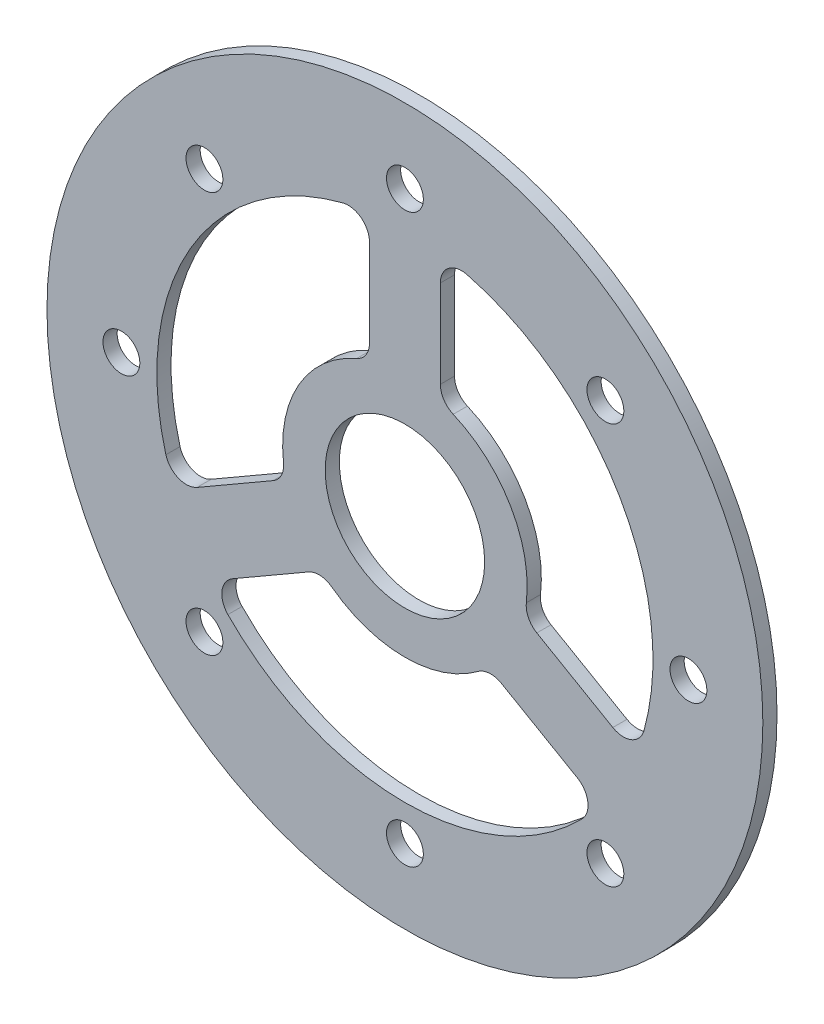
SolidWorks part; units mm, degrees
material "Thornel Mat VMA"
ref_plane "前视基准面" through (0, 0, 0) normal (0, 0, 1) x (1, 0, 0)
ref_plane "上视基准面" through (0, 0, 0) normal (0, 1, 0) x (1, 0, 0)
ref_plane "右视基准面" through (0, 0, 0) normal (1, 0, 0) x (0, 0, -1)
other "Configuration Table"
sketch "草图1" plane through (0, 0, 0) normal (0, 0, 1) x (1, 0, 0)
  circle A0 centre (0, 0) radius 40 construction
  circle A1 centre (0, 0) radius 50.5
  circle A2 centre (0, 40) radius 2.6
  circle A3 centre (0, 0) radius 35
  circle A4 centre (28.2843, 28.2843) radius 2.6
  circle A5 centre (40, 0) radius 2.6
  circle A6 centre (28.2843, -28.2843) radius 2.6
  circle A7 centre (0, -40) radius 2.6
  circle A8 centre (-28.2843, -28.2843) radius 2.6
  circle A9 centre (-40, 0) radius 2.6
  circle A10 centre (-28.2843, 28.2843) radius 2.6
  point P24 (0, 0)
  dimension "D1" = 80
  dimension "D2" = 101
  dimension "D3" = 70
  dimension "D4" = 5.2
  dimension "D5" = 8
extrude "凸台-拉伸1" add sketch "草图1" along normal blind 2
sketch "草图2" plane through (0, 0, 2) normal (0, 0, 1) x (1, 0, 0)
  line L0 (0, 35) -> (0, 17.25) construction
  line L1 (-5, 34.641) -> (-5, 17.25)
  line L2 (5, 34.641) -> (5, 17.25)
  line L3 (-5, 35) -> (-5, 17.25) construction
  line L4 (5, 35) -> (5, 17.25) construction
  line L5 (-5, 17.25) -> (-5, 16.5095)
  line L6 (5, 17.25) -> (5, 16.5095)
  line L7 (32.5, -12.9904) -> (17.4389, -4.2949)
  line L8 (27.5, -21.6506) -> (12.4389, -12.9551)
  line L9 (30.3109, -17.5) -> (14.9389, -8.625) construction
  line L10 (17.4389, -4.2949) -> (16.7976, -3.9246)
  line L11 (12.4389, -12.9551) -> (11.7976, -12.5849)
  line L12 (-27.5, -21.6506) -> (-12.4389, -12.9551)
  line L13 (-32.5, -12.9904) -> (-17.4389, -4.2949)
  line L14 (-30.3109, -17.5) -> (-14.9389, -8.625) construction
  line L15 (-12.4389, -12.9551) -> (-11.7976, -12.5849)
  line L16 (-17.4389, -4.2949) -> (-16.7976, -3.9246)
  circle A0 centre (0, 0) radius 17.5 construction
  circle A1 centre (0, 17.5) radius 2.55 construction
  circle A4 centre (15.1554, -8.75) radius 2.55 construction
  circle A5 centre (-15.1554, -8.75) radius 2.55 construction
  circle A6 centre (0, 0) radius 11.25
  circle A7 centre (0, 0) radius 17.25
  circle A8 centre (0, 0) radius 35 construction
  circle A10 centre (0, 0) radius 35
  point P12 (0, 0)
  point P43 (0, 0)
  circle M5 centre (0, 0) radius 35
  dimension "D1" = 35
  dimension "D2" = 3
  dimension "D3" = 5.1
  dimension "D4" = 22.5
  dimension "D5" = 6
  dimension "D6" = 5
  dimension "D8" = 3
  dimension "D7" = 5
extrude "凸台-拉伸3" add sketch "草图2" against normal up to surface (2 mm away) contours A7 L6 L2 L1 L5 M5 | A7 A6 A5 A4 A1 | A7 L16 L13 L12 L15 M5 | A7 L11 L8 L7 L10 M5
fillet "圆角1" radius 3 12 edges at (32.5, -12.9904, 1) (16.7976, -3.9246, 1) (5, 16.5095, 1) (5, 34.641, 1) (-11.7976, -12.5849, 1) (11.7976, -12.5849, 1) (27.5, -21.6506, 1) (-5, 16.5095, 1) (-16.7976, -3.9246, 1) (-32.5, -12.9904, 1) (-5, 34.641, 1) (-27.5, -21.6506, 1)
